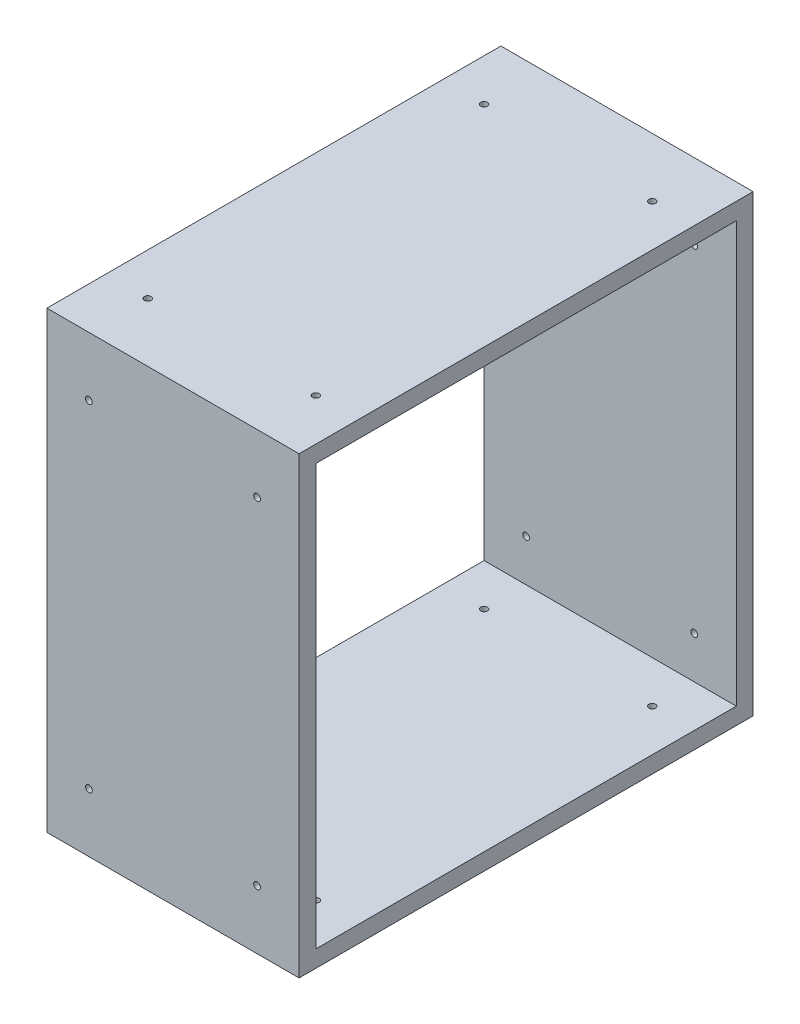
SolidWorks part; units mm, degrees
ref_plane "前视基准面" through (0, 0, 0) normal (0, 0, 1) x (1, 0, 0)
ref_plane "上视基准面" through (0, 0, 0) normal (0, 1, 0) x (1, 0, 0)
ref_plane "右视基准面" through (0, 0, 0) normal (1, 0, 0) x (0, 0, -1)
other "Configuration Table"
sketch "草图1" plane through (0, 0, 0) normal (1, 0, 0) x (0, 0, -1)
  line L2 (-250, 0) -> (-250, 250)
  line L5 (-270, 270) -> (-250, 250)
  line L8 (-270, 0) -> (-270, 270)
  line L13 (-250, 0) -> (-270, 0)
  point P0 (0, 0)
  point P6 (0, 0)
  dimension "D1" = 20
  dimension "D2" = 250
  dimension "D3" = 250
extrude "凸台-拉伸1" add sketch "草图1" along normal blind 300
sketch "草图2" plane through (0, 0, 250) normal (0, 0, -1) x (-1, 0, 0)
  line L0 (-300, 200) -> (-250, 200) construction
  line L1 (-300, 0) -> (-300, 250) construction
  line L2 (-250, 200) -> (-50, 200) construction
  line L3 (-50, 200) -> (0, 200) construction
  line L4 (0, 0) -> (0, 250) construction
  line L5 (-250, 200) -> (-250, 250) construction
  line L7 (-300, 250) -> (0, 250) construction
  circle A0 centre (-250, 200) radius 4
  circle A1 centre (-50, 200) radius 4
  dimension "D1" = 8
  dimension "D2" = 50
extrude "切除-拉伸1" cut sketch "草图2" against normal through all
mirror "镜向1" about plane through (300, 270, 270) normal (0, -0.7071, 0.7071) of bodies 107
mirror "镜向2" about plane through (300, 250, 0) normal (0, 0, 1) of bodies 108
mirror "镜向3" about plane through (300, 0, -250) normal (0, 1, 0) of bodies 109
